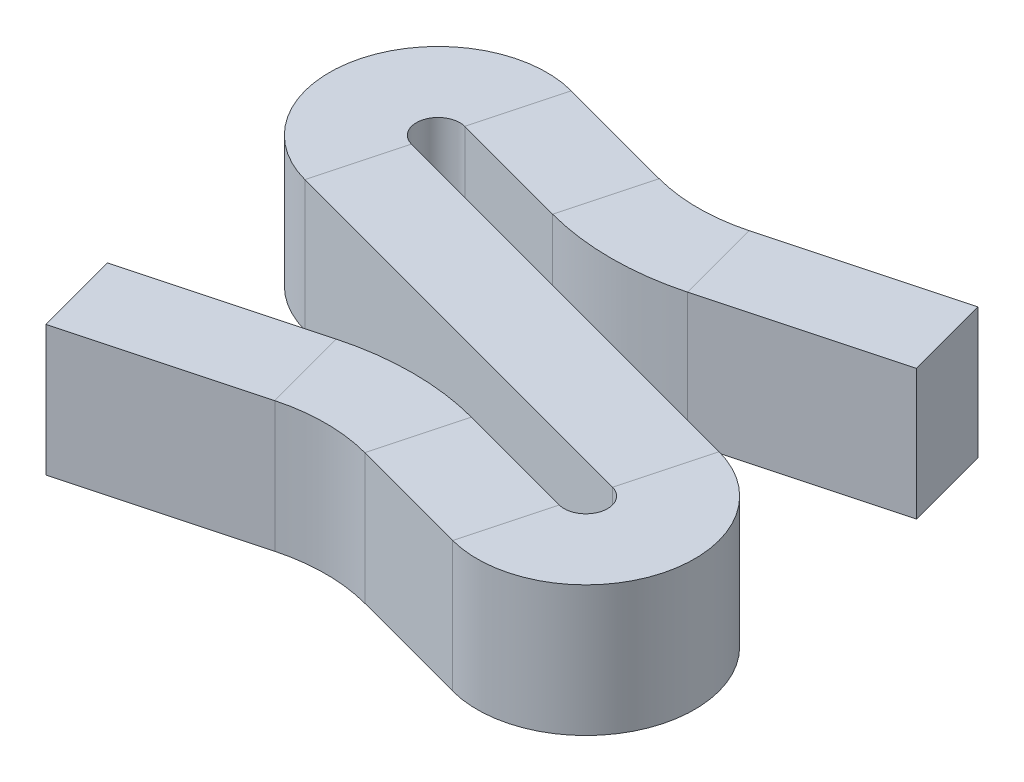
SolidWorks part; units mm, degrees
ref_plane "Płaszczyzna przednia" through (0, 0, 0) normal (0, 0, 1) x (1, 0, 0)
ref_plane "Płaszczyzna górna" through (0, 0, 0) normal (0, 1, 0) x (1, 0, 0)
ref_plane "Płaszczyzna prawa" through (0, 0, 0) normal (1, 0, 0) x (0, 0, -1)
sketch "Sketch1" plane through (0, 0, 0) normal (0, 1, 0) x (1, 0, 0)
  line L0 (-4.8296, 1.2941) -> (4.8296, -1.2941)
  line L1 (-4.0532, 4.1919) -> (-1.2941, 3.4526)
  line L2 (1.2941, 3.4526) -> (5.4414, 4.5638)
  line L3 (0, 0) -> (-21.1869, 0) construction
  line L4 (4.0532, -4.1919) -> (1.2941, -3.4526)
  line L5 (-1.2941, -3.4526) -> (-5.4414, -4.5638)
  line L6 (0, 0) -> (0, 3.1058) construction
  line L7 (-5.9414, 5.1967) -> (-5.9414, -5.4211) construction
  arc A0 (-4.8296, 1.2941) -> (-4.0532, 4.1919) centre (-4.4414, 2.743) cw
  arc A1 (4.8296, -1.2941) -> (4.0532, -4.1919) centre (4.4414, -2.743) cw
  arc A2 (1.2941, -3.4526) -> (-1.2941, -3.4526) centre (0, -8.2822) ccw
  arc A3 (-1.2941, 3.4526) -> (1.2941, 3.4526) centre (0, 8.2822) ccw
  point P4 (0, 0)
  dimension "D2" = 1.5
  dimension "D5" = 0.5
  dimension "D6" = 5
  dimension "D1" = 15
  dimension "D3" = 10
  dimension "D4" = 15
ref_plane "Plane1" through (-5.4414, 0, 4.5638) normal (-0.9659, 0, 0.2588) x (0.2588, 0, 0.9659)
sketch "Sketch2" plane through (-5.4414, 0, 4.5638) normal (-0.9659, 0, 0.2588) x (0.2588, 0, 0.9659)
  line L1 (-1, -1.5) -> (1, -1.5)
  line L2 (-1, -1.5) -> (-1, 1.5)
  line L3 (-1, 1.5) -> (1, 1.5)
  line L4 (1, -1.5) -> (1, 1.5)
  line L5 (-1, -1.5) -> (1, 1.5) construction
  line L6 (-1, 1.5) -> (1, -1.5) construction
  point P0 (0, 0)
  dimension "D1" = 3
  dimension "D2" = 2
sweep "Sweep1" add profiles "Sketch2" path "Sketch1"
